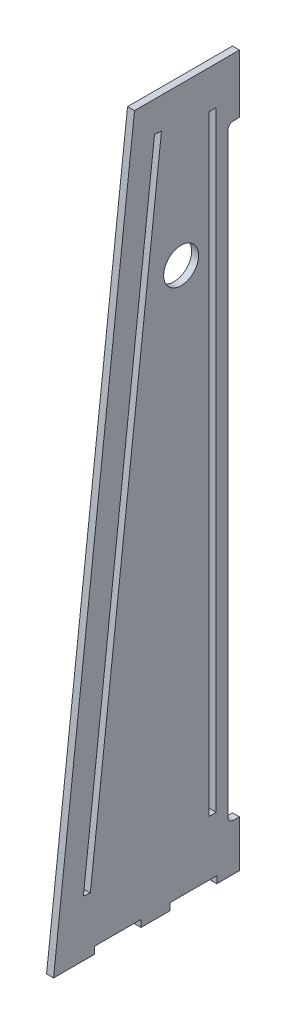
SolidWorks part; units mm, degrees
ref_plane "Front Plane" through (0, 0, 0) normal (1, 0, 0) x (0, 1, 0)
ref_plane "Top Plane" through (0, 0, 0) normal (0, 0, 1) x (0, 1, 0)
ref_plane "Right Plane" through (0, 0, 0) normal (0, 1, 0) x (-1, 0, 0)
sketch "Sketch1" plane through (0, 0, 0) normal (1, 0, 0) x (0, 1, 0)
  line L0 (-165.8114, 45.9585) -> (-165.8114, 10.9585)
  line L1 (-165.8114, -113.4967) -> (-125.8114, -113.4967)
  line L2 (443.7886, -113.4967) -> (443.7886, -23.4967)
  line L3 (443.7886, -23.4967) -> (-165.8114, 45.9585)
  line L4 (443.7886, -23.4967) -> (263.0681, -23.4967) construction
  line L5 (-165.8114, 25.8291) -> (443.7886, -43.6261) construction
  line L6 (-165.8114, 19.7902) -> (443.7886, -49.6649) construction
  line L7 (-117.7615, 20.3545) -> (-118.4407, 14.393)
  line L8 (-118.4407, 14.393) -> (416.9886, -46.6114)
  line L9 (416.9886, -46.6114) -> (417.6678, -40.65)
  line L10 (417.6678, -40.65) -> (-117.7615, 20.3545)
  line L11 (-216.2642, 25.5386) -> (494.4656, -55.4388) construction
  line L12 (-215.5849, 31.5) -> (495.1448, -49.4774) construction
  line L13 (-159.8114, 82.9795) -> (-159.8114, -136.3635) construction
  line L14 (-165.8114, 10.9585) -> (-159.8114, 10.9585)
  line L15 (-159.8114, 10.9585) -> (-159.8114, -29.0415)
  line L16 (-159.8114, -29.0415) -> (-165.8114, -29.0415)
  line L17 (-165.8114, -54.0415) -> (-159.8114, -54.0415)
  line L18 (-159.8114, -54.0415) -> (-159.8114, -94.0415)
  line L19 (-159.8114, -94.0415) -> (-165.8114, -94.0415)
  line L20 (-165.8114, -29.0415) -> (-165.8114, -54.0415)
  line L21 (-165.8114, -94.0415) -> (-165.8114, -113.4967)
  line L22 (-125.8114, -113.4967) -> (-125.8114, -108.4967)
  line L23 (-112.4497, -87.4967) -> (411.0033, -87.4967)
  line L24 (-112.4497, -87.4967) -> (-112.4497, -93.4967)
  line L25 (-112.4497, -93.4967) -> (411.0033, -93.4967)
  line L26 (411.0033, -87.4967) -> (411.0033, -93.4967)
  line L27 (-120.8114, -103.4967) -> (388.7886, -103.4967)
  line L28 (393.7886, -108.4967) -> (393.7886, -113.4967)
  line L29 (393.7886, -113.4967) -> (443.7886, -113.4967)
  circle A0 centre (308.7886, -63.4967) radius 15
  arc A1 (-120.8114, -103.4967) -> (-125.8114, -108.4967) centre (-120.8114, -108.4967) ccw
  arc A2 (393.7886, -108.4967) -> (388.7886, -103.4967) centre (388.7886, -108.4967) ccw
  dimension "D15" = 30
  dimension "D19" = 5
  dimension "D20" = 5
  dimension "D1" = 609.6
  dimension "D2" = 135
  dimension "D3" = 50
  dimension "D4" = 6.5
  dimension "D5" = 90
  dimension "D6" = 20
  dimension "D8" = 6
  dimension "D9" = 40
  dimension "D10" = 35
  dimension "D11" = 40
  dimension "D12" = 25
  dimension "D13" = 6
  dimension "D14" = 20
  dimension "D16" = 40
  dimension "D17" = 50
  dimension "D18" = 10
  dimension "D7" = 6
extrude "Boss-Extrude1" add sketch "Sketch1" along normal blind 6
